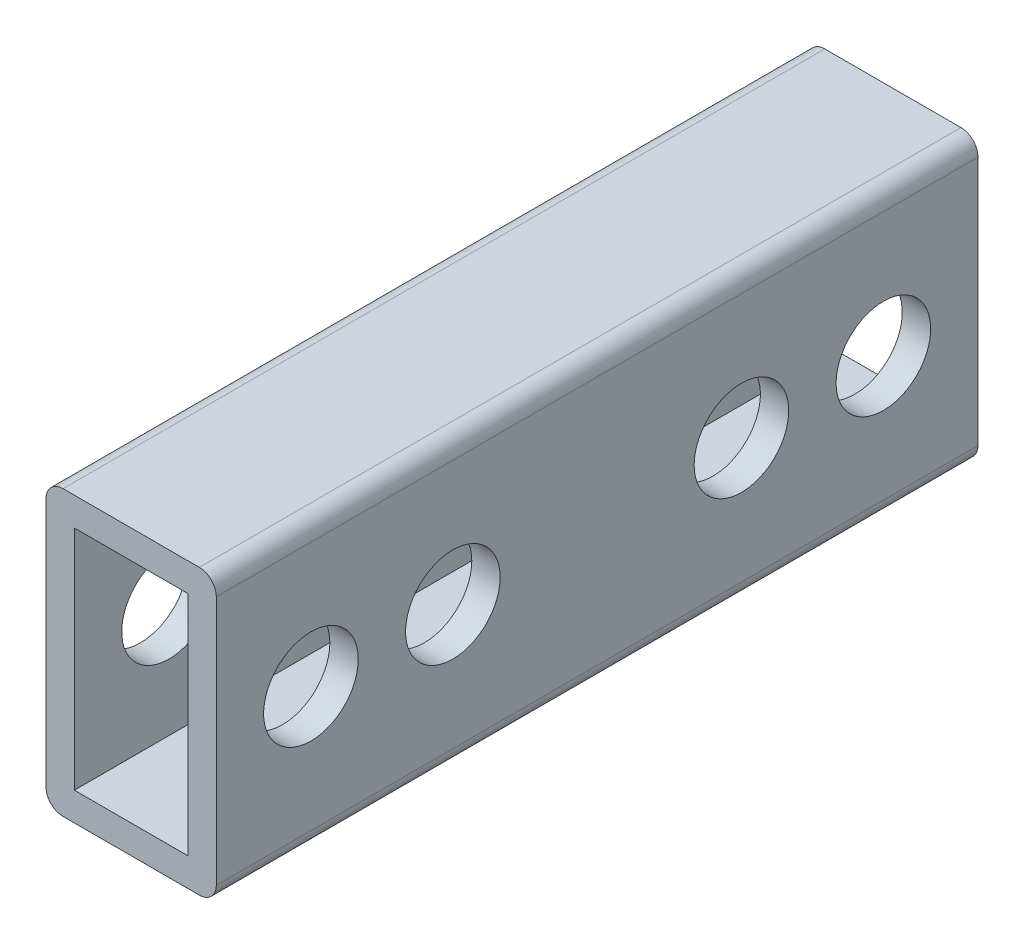
SolidWorks part; units mm, degrees
material "6061-T6 (SS)"
ref_plane "Front Plane" through (0, 0, 0) normal (0, 0, 1) x (1, 0, 0)
ref_plane "Top Plane" through (0, 0, 0) normal (0, 1, 0) x (1, 0, 0)
ref_plane "Right Plane" through (0, 0, 0) normal (1, 0, 0) x (0, 0, -1)
sketch "Sketch1" plane through (0, 0, 0) normal (0, 0, 1) x (1, 0, 0)
  line L1 (9, -15) -> (-9, -15)
  line L2 (9, -15) -> (9, 15)
  line L3 (9, 15) -> (-9, 15)
  line L4 (-9, -15) -> (-9, 15)
  line L5 (9, -15) -> (-9, 15) construction
  line L6 (9, 15) -> (-9, -15) construction
  line L7 (6, -12) -> (-6, -12)
  line L8 (6, -12) -> (6, 12)
  line L9 (6, 12) -> (-6, 12)
  line L10 (-6, -12) -> (-6, 12)
  line L11 (6, -12) -> (-6, 12) construction
  line L12 (6, 12) -> (-6, -12) construction
  point P0 (0, 0)
  point P6 (0, 0)
  dimension "D1" = 30
  dimension "D2" = 18
  dimension "D3" = 3
  dimension "D4" = 3
extrude "Body" add sketch "Sketch1" along normal blind 80.5
sketch "Sketch2" plane through (9, 0, 0) normal (1, 0, 0) x (0, 0, -1)
  line L0 (0, 0) -> (-80.5, 0) construction
  line L1 (-80.5, -15) -> (-80.5, 15) construction
  line L2 (-40.25, -15) -> (-40.25, 15) construction
  line L3 (-80.5, -15) -> (0, -15) construction
  line L4 (-80.5, 15) -> (0, 15) construction
  circle A0 centre (-70.5, 0) radius 5
  circle A1 centre (-55.5, 0) radius 5
  circle A2 centre (-25, 0) radius 5
  circle A3 centre (-10, 0) radius 5
  dimension "D1" = 10
  dimension "D2" = 10
  dimension "D3" = 10
  dimension "D4" = 15
extrude "Mount Holes" cut sketch "Sketch2" against normal through all
fillet "Corner Fillets" radius 1.8 4 edges at (-9, -15, 40.25) (9, -15, 40.25) (9, 15, 40.25) (-9, 15, 40.25)
equation "\"linkage_thickness\"= 18.0mm"
equation "\"width\"= 30.0mm"
equation "\"wall_thickness\"= 3.0mm"
equation "\"length\"= 80.5mm"
equation "\"angle\"= 0"
equation "\"bolt_diameter\"= 10.0mm"
equation "\"bolt_spacing\"= 5.0mm"
equation "\"D1@Sketch1\"=\"width\""
equation "\"D2@Sketch1\"=\"linkage_thickness\""
equation "\"D3@Sketch1\"=\"wall_thickness\""
equation "\"D4@Sketch1\"=\"wall_thickness\""
equation "\"D1@Body\"=\"length\""
equation "\"D1@Sketch2\"=\"bolt_diameter\""
equation "\"D2@Sketch2\"=\"bolt_diameter\""
equation "\"D3@Sketch2\"=\"bolt_spacing\"+\"bolt_diameter\"/2"
equation "\"D4@Sketch2\"=\"bolt_spacing\"+\"bolt_diameter\""
equation "\"D1@Corner Fillets\"=\"linkage_thickness\"/10"
